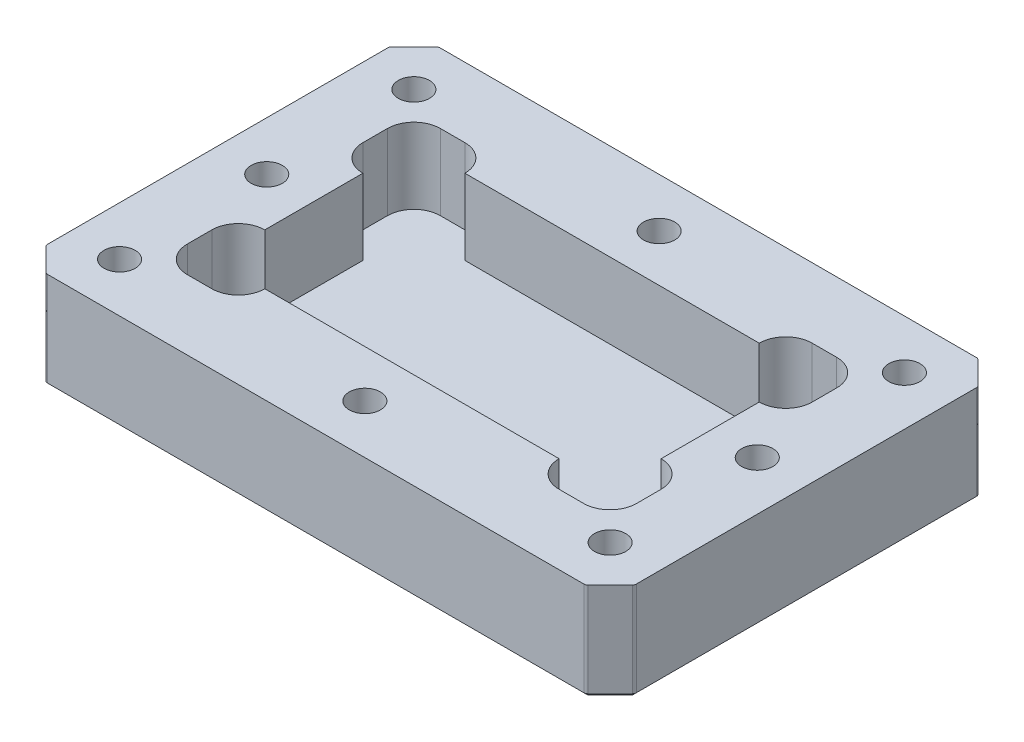
SolidWorks part; units mm, degrees
material "6061-T6 (SS)"
ref_plane "Front Plane" through (0, 0, 0) normal (0, 0, 1) x (1, 0, 0)
ref_plane "Top Plane" through (0, 0, 0) normal (0, 1, 0) x (1, 0, 0)
ref_plane "Right Plane" through (0, 0, 0) normal (1, 0, 0) x (0, 0, -1)
sketch "Sketch1" plane through (0, 0, 0) normal (0, 1, 0) x (1, 0, 0)
  line L1 (-38.1, 25.4) -> (38.1, 25.4)
  line L2 (-38.1, 25.4) -> (-38.1, -25.4)
  line L3 (-38.1, -25.4) -> (38.1, -25.4)
  line L4 (38.1, 25.4) -> (38.1, -25.4)
  line L5 (-38.1, 25.4) -> (38.1, -25.4) construction
  line L6 (-38.1, -25.4) -> (38.1, 25.4) construction
  point P0 (0, 0)
  dimension "D1" = 76.2
  dimension "D2" = 50.8
extrude "Boss-Extrude1" add sketch "Sketch1" along normal blind 12.7
sketch "Sketch2" plane through (0, 12.7, 0) normal (0, 1, 0) x (1, 0, 0)
  line L1 (-25.654, 12.954) -> (25.654, 12.954)
  line L2 (-25.654, 12.954) -> (-25.654, -12.954)
  line L3 (-25.654, -12.954) -> (25.654, -12.954)
  line L4 (25.654, 12.954) -> (25.654, -12.954)
  line L5 (-25.654, 12.954) -> (25.654, -12.954) construction
  line L6 (-25.654, -12.954) -> (25.654, 12.954) construction
  point P0 (0, 0)
  dimension "D1" = 51.308
  dimension "D2" = 25.908
extrude "Cut-Extrude1" cut sketch "Sketch2" against normal blind 9.779
sketch "Sketch3" plane through (0, 12.7, 0) normal (0, 1, 0) x (1, 0, 0)
  line L0 (25.654, 12.954) -> (-25.654, 12.954) construction
  line L2 (-25.654, 12.954) -> (-25.654, -12.954) construction
  line L3 (-22.479, 16.383) -> (-25.654, 16.383)
  line L4 (-29.083, 12.954) -> (-29.083, 9.779)
  line L6 (-23.2293, 7.3543) -> (-20.0543, 10.5293)
  line L7 (25.654, 12.954) -> (-25.654, 12.954) construction
  arc A0 (-20.0543, 10.5293) -> (-22.479, 16.383) centre (-22.479, 12.954) ccw
  arc A1 (-29.083, 9.779) -> (-23.2293, 7.3543) centre (-25.654, 9.779) ccw
  arc A2 (-25.654, 16.383) -> (-29.083, 12.954) centre (-25.654, 12.954) ccw
  dimension "D1" = 3.429
  dimension "D2" = 3.175
  dimension "D3" = 3.175
extrude "Cut-Extrude2" cut sketch "Sketch3" against normal up to surface (9.779 mm away) up to face at (0, 2.921, 0)
mirror "Mirror1" about plane through (0, 0, 0) normal (0, 0, 1) of "Cut-Extrude2"
mirror "Mirror2" about plane through (0, 0, 0) normal (1, 0, 0) of "Mirror1", "Cut-Extrude2"
hole_wizard "#10-32 Tapped Hole1" positions "Sketch4" profile "Sketch5" tap size "#10-32" standard "ANSI Inch" end condition through all
sketch "Sketch4" plane through (0, 12.7, 0) normal (0, 1, 0) x (1, 0, 0)
  line L0 (-31.75, 19.05) -> (31.75, -19.05) construction
  line L3 (31.75, 19.05) -> (-31.75, -19.05) construction
  point P0 (-31.75, 19.05)
  point P2 (31.75, 19.05)
  point P4 (31.75, -19.05)
  point P6 (-31.75, -19.05)
  dimension "D1" = 63.5
  dimension "D2" = 38.1
sketch "Sketch5" plane through (-31.75, 12.7, -19.05) normal (1, 0, 0) x (0, 0, 1)
  line L0 (0, 0) -> (0, 12.7)
  line L1 (0, 12.7) -> (2.0193, 12.7)
  line L2 (2.0193, 12.7) -> (2.0193, 0)
  line L5 (2.0193, 0) -> (0, 0)
  line L11 (0, -6.35) -> (0, 107.95) construction
  dimension "Thru Tap Drill Dia." = 4.0386
  dimension "Thru Tap Drill Depth" = 12.7
cosmetic thread "Hole Thread1" parameters "D2"=4.826
cosmetic thread "Hole Thread2" parameters "D2"=4.826
cosmetic thread "Hole Thread3" parameters "D2"=4.826
cosmetic thread "Hole Thread4" parameters "D2"=4.826
chamfer "Chamfer1" distance 3.175 angle 45 4 edges at (-38.1, 6.35, -25.4) (38.1, 6.35, -25.4) (38.1, 6.35, 25.4) (-38.1, 6.35, 25.4)
fillet "Fillet1" radius 0.508 8 edges at (38.1, 6.35, -22.225) (34.925, 6.35, -25.4) (-34.925, 6.35, -25.4) (-38.1, 6.35, -22.225) (-34.925, 6.35, 25.4) (-38.1, 6.35, 22.225) (38.1, 6.35, 22.225) (34.925, 6.35, 25.4)
chamfer "Chamfer2" distance 0.508 angle 45 16 edges at (-36.5125, 0, 23.8125) (-38.1, 0, 0) (-36.5125, 0, -23.8125) (0, 0, -25.4) (36.5125, 0, -23.8125) (38.1, 0, 0) (36.5125, 0, 23.8125) (0, 0, 25.4) (-34.909, 0, -25.3613) (34.909, 0, -25.3613) (-38.0613, 0, -22.209) (38.0613, 0, -22.209) (-38.0613, 0, 22.209) (38.0613, 0, 22.209) (-34.909, 0, 25.3613) (34.909, 0, 25.3613)
hole_wizard "#10-32 Tapped Hole2" positions "Sketch6" profile "Sketch7" tap size "#10-32" standard "ANSI Inch" end condition through all
sketch "Sketch6" plane through (0, 0, 0) normal (0, -1, 0) x (-1, 0, 0)
  line L0 (0, 19.05) -> (0, -19.05)
  line L3 (31.75, 0) -> (-31.75, 0)
  point P0 (0, 19.05)
  point P2 (0, -19.05)
  point P4 (31.75, 0)
  point P6 (-31.75, 0)
  dimension "D1" = 63.5
  dimension "D2" = 38.1
sketch "Sketch7" plane through (0, 0, -19.05) normal (1, 0, 0) x (0, 0, -1)
  line L0 (0, 0) -> (0, 12.7)
  line L1 (0, 12.7) -> (2.0193, 12.7)
  line L2 (2.0193, 12.7) -> (2.0193, 0)
  line L5 (2.0193, 0) -> (0, 0)
  line L11 (0, -6.35) -> (0, 107.95) construction
  dimension "Thru Tap Drill Dia." = 4.0386
  dimension "Thru Tap Drill Depth" = 12.7
cosmetic thread "Hole Thread5" parameters "D2"=4.826
cosmetic thread "Hole Thread6" parameters "D2"=4.826
cosmetic thread "Hole Thread7" parameters "D2"=4.826
cosmetic thread "Hole Thread8" parameters "D2"=4.826
